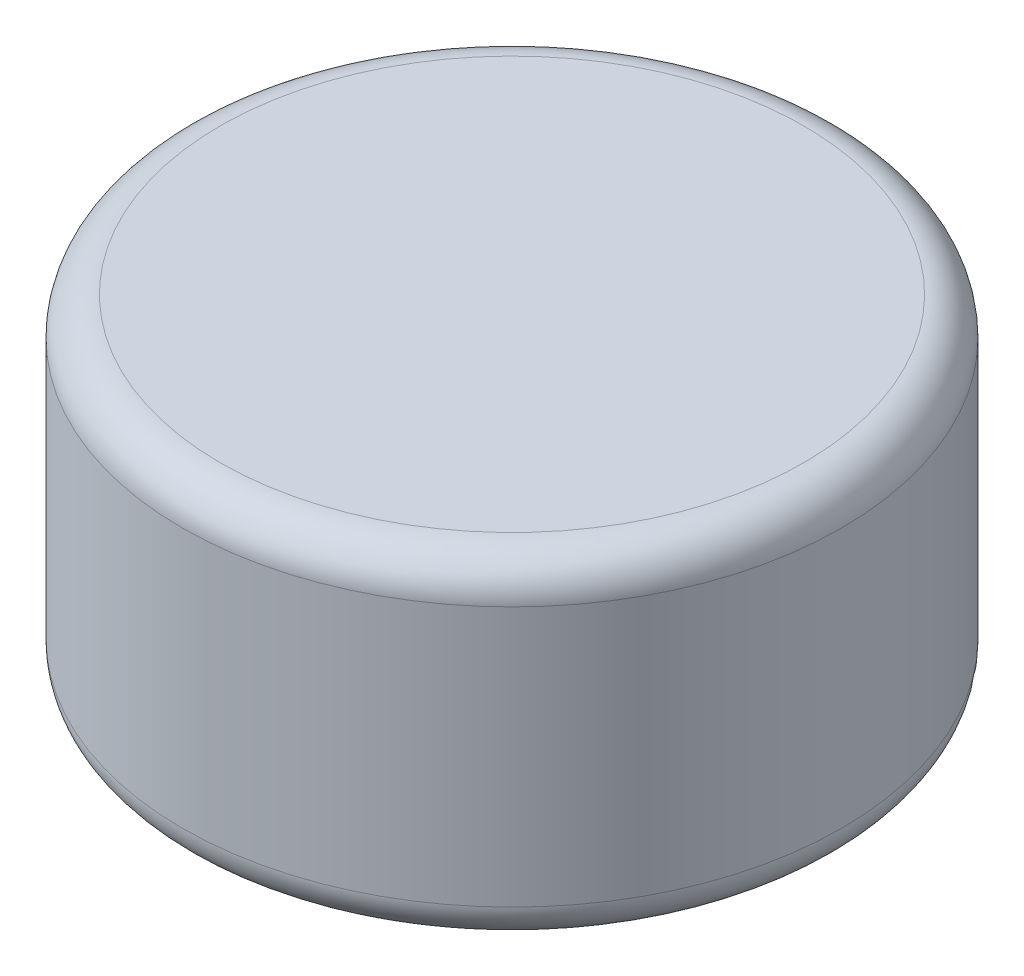
SolidWorks part; units mm, degrees
ref_plane "Piano frontale" through (0, 0, 0) normal (1, 0, 0) x (0, 1, 0)
ref_plane "Piano superiore" through (0, 0, 0) normal (0, 0, 1) x (0, 1, 0)
ref_plane "Piano destro" through (0, 0, 0) normal (0, 1, 0) x (-1, 0, 0)
sketch "Schizzo1" plane through (0, 0, 0) normal (0, 1, 0) x (-1, 0, 0)
  circle A0 centre (0, 0) radius 349.25
  dimension "D1" = 698.5
extrude "Estrusione-Estrusione1" add sketch "Schizzo1" along normal blind 355.6 contours A0
fillet "Raccordo1" radius 40 2 edges at (0, 0, 349.25) (0, 355.6, 349.25)
sketch "Schizzo2" plane through (0, 0, 0) normal (0, -1, 0) x (1, 0, 0)
  circle A0 centre (0, 0) radius 65.5
  dimension "D1" = 131
extrude "Taglio-Estrusione1" cut sketch "Schizzo2" against normal blind 136
